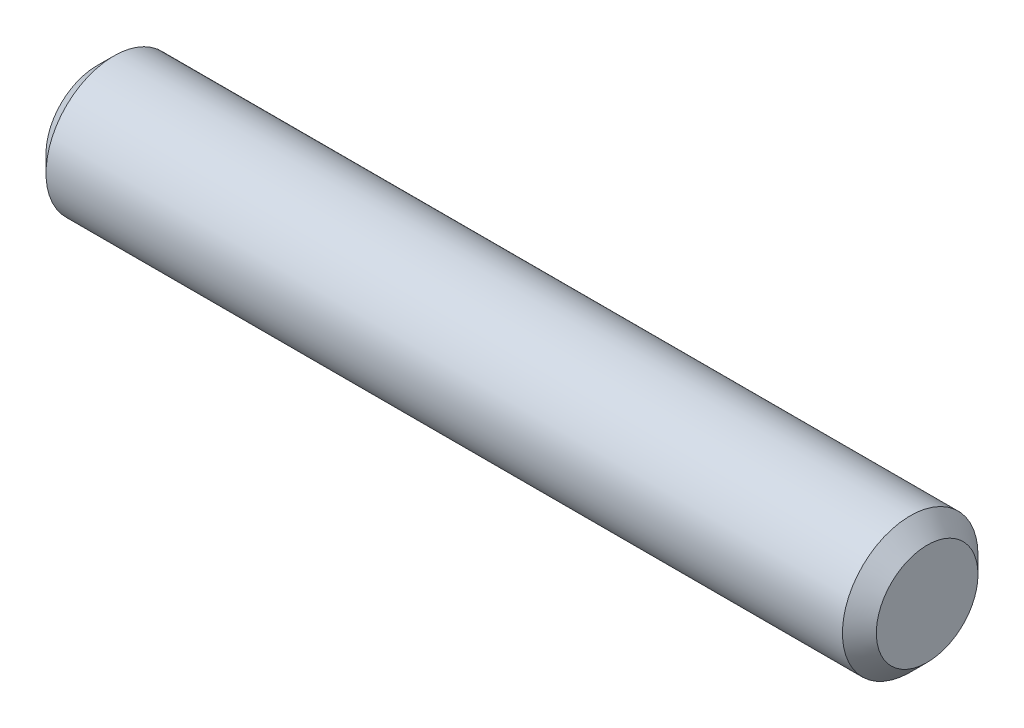
SolidWorks part; units mm, degrees
material "AISI 1020"
ref_plane "Front Plane" through (0, 0, 0) normal (0, 0, 1) x (1, 0, 0)
ref_plane "Top Plane" through (0, 0, 0) normal (0, 1, 0) x (1, 0, 0)
ref_plane "Right Plane" through (0, 0, 0) normal (1, 0, 0) x (0, 0, -1)
sketch "Sketch1" plane through (0, 0, 0) normal (1, 0, 0) x (0, 0, -1)
  circle A0 centre (0, 0) radius 4
  dimension "D1" = 8
extrude "Boss-Extrude1" add sketch "Sketch1" along normal mid plane 49
chamfer "Chamfer1" distance 1 angle 45 2 edges at (-24.5, 0, -4) (24.5, 0, -4)
